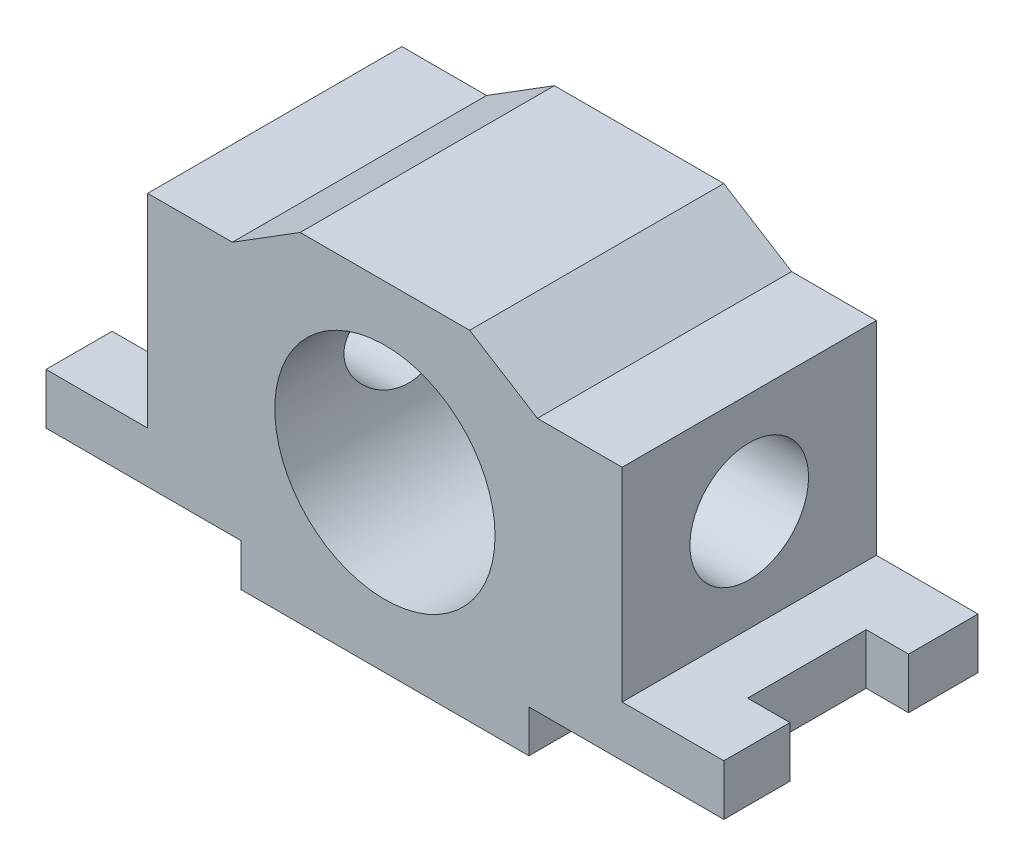
SolidWorks part; units mm, degrees
ref_plane "Front Plane" through (0, 0, 0) normal (0, 0, 1) x (1, 0, 0)
ref_plane "Top Plane" through (0, 0, 0) normal (0, 1, 0) x (1, 0, 0)
ref_plane "Right Plane" through (0, 0, 0) normal (1, 0, 0) x (0, 0, -1)
sketch "Sketch1" plane through (0, 0, 0) normal (0, 0, 1) x (1, 0, 0)
  line L0 (-40, 0) -> (-17, 0)
  line L2 (-17, -5) -> (17, -5)
  line L3 (-17, -5) -> (-17, 0)
  line L4 (17, -5) -> (17, 0)
  line L5 (-40, 6) -> (-28, 6)
  line L6 (28, 6) -> (40, 6)
  line L7 (28, 6) -> (28, 30)
  line L8 (40, 6) -> (40, 0)
  line L9 (-28, 6) -> (-28, 30)
  line L10 (-40, 6) -> (-40, 0)
  line L11 (17, 0) -> (40, 0)
  line L12 (-28, 30) -> (-18, 30)
  line L13 (-10, 35) -> (10, 35)
  line L16 (-18, 30) -> (-10, 35)
  line L17 (10, 35) -> (18, 30)
  line L22 (18, 30) -> (28, 30)
  line L23 (0, 35) -> (0, 40) construction
  point P3 (0, 0)
  point P6 (0, 0)
  point P9 (0, -5)
  point P18 (0, 6)
  point P22 (0, 30)
  point P23 (0, 35)
  dimension "D1" = 80
  dimension "D6" = 80
  dimension "D2" = 5
  dimension "D3" = 34
  dimension "D7" = 80
  dimension "D8" = 6
  dimension "D4" = 35
  dimension "D5" = 20
  dimension "D9" = 40
  dimension "D10" = 24
extrude "Boss-Extrude1" add sketch "Sketch1" along normal mid plane 30
sketch "Sketch2" plane through (0, 0, 15) normal (0, 0, 1) x (1, 0, 0)
  circle A0 centre (0, 15.4747) radius 13
  dimension "D1" = 26
extrude "Cut-Extrude1" cut sketch "Sketch2" against normal blind 30
sketch "Sketch3" plane through (0, 6, 0) normal (0, 1, 0) x (1, 0, 0)
  line L0 (40, -15) -> (40, 15) construction
  line L1 (40, 6.802) -> (35, 6.802)
  line L2 (40, 6.802) -> (40, -7.198)
  line L3 (40, -7.198) -> (35, -7.198)
  line L4 (35, 6.802) -> (35, -7.198)
  dimension "D1" = 14
  dimension "D2" = 5
extrude "Cut-Extrude2" cut sketch "Sketch3" against normal up to next
mirror "Mirror1" about plane through (0, 0, 0) normal (1, 0, 0) of "Cut-Extrude2"
sketch "Sketch4" plane through (28, 0, 0) normal (1, 0, 0) x (0, 0, -1)
  circle A0 centre (0, 18) radius 7
  dimension "D1" = 14
extrude "Cut-Extrude3" cut sketch "Sketch4" against normal through all both and the other way through all
